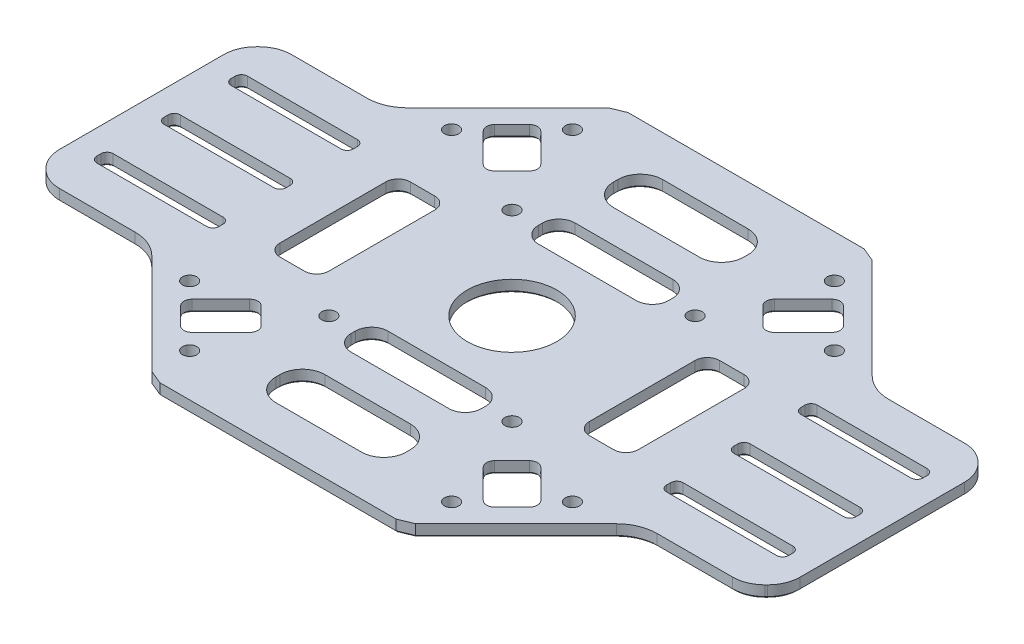
SolidWorks part; units mm, degrees
ref_plane "Спереди" through (0, 0, 0) normal (0, 0, 1) x (1, 0, 0)
ref_plane "Сверху" through (0, 0, 0) normal (0, 1, 0) x (1, 0, 0)
ref_plane "Справа" through (0, 0, 0) normal (1, 0, 0) x (0, 0, -1)
sketch "Эскиз1" plane through (0, 0, 0) normal (0, 1, 0) x (1, 0, 0)
  line L0 (-47.2118, 0) -> (134.7882, 0) construction
  line L1 (43.7882, -85.4485) -> (43.7882, 85.4485) construction
  line L2 (74.6039, 30.8143) -> (88.0389, 44.2493) construction
  line L3 (-47.2118, -20.1863) -> (-47.2118, 20.1863)
  line L4 (43.7882, 0) -> (74.6039, 30.8143) construction
  line L5 (59.7882, 23.5) -> (59.7882, 22.5)
  line L6 (-44.8686, 25.8431) -> (-44.5549, 26.1569)
  line L7 (72.7882, 57.5) -> (76.2024, 56.0858)
  line L8 (100.8593, 31.4289) -> (76.2024, 56.0858)
  line L9 (72.4825, 32.9356) -> (76.7252, 28.693)
  line L10 (86.6247, 35.7641) -> (79.5536, 28.693)
  line L11 (79.5536, 42.8351) -> (72.4825, 35.7641)
  line L12 (-38.8981, 28.5) -> (-20.3539, 28.5)
  line L13 (84.5034, 40.7138) -> (86.6247, 38.5925)
  line L14 (71.7882, 57.5) -> (15.7882, 57.5)
  line L15 (59.7882, 42) -> (59.7882, 41)
  line L16 (15.7882, 57.5) -> (14.7882, 57.5)
  line L17 (84.5034, 40.7138) -> (82.382, 42.8351)
  line L18 (75.7882, -13) -> (75.7882, 13)
  line L19 (-39.7118, 2) -> (-12.7118, 2)
  line L20 (-41.2118, 0.5) -> (-41.2118, -0.5)
  line L21 (84.7882, 16) -> (78.7882, 16)
  line L22 (-11.2118, 0.5) -> (-11.2118, -0.5)
  line L23 (87.7882, -13) -> (87.7882, 13)
  line L24 (100.2882, 18.5) -> (127.2882, 18.5)
  line L25 (127.2882, 14.5) -> (100.2882, 14.5)
  line L26 (128.7882, 17) -> (128.7882, 16)
  line L27 (98.7882, 16) -> (98.7882, 17)
  line L28 (98.7882, 0.5) -> (98.7882, -0.5)
  line L29 (128.7882, 0.5) -> (128.7882, -0.5)
  line L30 (127.2882, 2) -> (100.2882, 2)
  line L31 (71.7882, 57.5) -> (72.7882, 57.5)
  line L32 (126.4745, 28.5) -> (107.9304, 28.5)
  line L33 (132.4451, 25.8431) -> (132.1314, 26.1569)
  line L34 (134.7882, -20.1863) -> (134.7882, 20.1863)
  line L35 (12.9726, -30.8143) -> (-0.4624, -44.2493) construction
  line L36 (43.7882, 0) -> (12.9726, -30.8143) construction
  line L37 (43.7882, 0) -> (74.6039, -30.8143) construction
  line L38 (74.6039, -30.8143) -> (88.0389, -44.2493) construction
  line L39 (31.7882, -18.5) -> (55.7882, -18.5)
  line L40 (27.7882, -23.5) -> (27.7882, -22.5)
  line L41 (31.7882, -27.5) -> (55.7882, -27.5)
  line L42 (14.7882, -57.5) -> (11.374, -56.0858)
  line L43 (-13.2828, -31.4289) -> (11.374, -56.0858)
  line L44 (15.0939, -32.9356) -> (10.8513, -28.693)
  line L45 (0.9518, -35.7641) -> (8.0229, -28.693)
  line L46 (8.0229, -42.8351) -> (15.0939, -35.7641)
  line L47 (3.0731, -40.7138) -> (0.9518, -38.5925)
  line L48 (33.2882, -35.5) -> (54.2882, -35.5)
  line L49 (27.7882, -42) -> (27.7882, -41)
  line L50 (-11.2118, 16) -> (-11.2118, 17)
  line L51 (-41.2118, 17) -> (-41.2118, 16)
  line L52 (-39.7118, 14.5) -> (-12.7118, 14.5)
  line L53 (-12.7118, 18.5) -> (-39.7118, 18.5)
  line L54 (54.2882, -47.5) -> (33.2882, -47.5)
  line L55 (3.0731, -40.7138) -> (5.1944, -42.8351)
  line L56 (2.7882, -16) -> (8.7882, -16)
  line L57 (-12.7118, -18.5) -> (-39.7118, -18.5)
  line L58 (-39.7118, -14.5) -> (-12.7118, -14.5)
  line L59 (-41.2118, -17) -> (-41.2118, -16)
  line L60 (-11.2118, -16) -> (-11.2118, -17)
  line L61 (-0.2118, -13) -> (-0.2118, 13)
  line L62 (2.7882, 16) -> (8.7882, 16)
  line L63 (11.7882, -13) -> (11.7882, 13)
  line L64 (132.4451, -25.8431) -> (132.1314, -26.1569)
  line L65 (126.4745, -28.5) -> (107.9304, -28.5)
  line L66 (71.7882, -57.5) -> (72.7882, -57.5)
  line L67 (127.2882, -2) -> (100.2882, -2)
  line L68 (98.7882, -16) -> (98.7882, -17)
  line L69 (128.7882, -17) -> (128.7882, -16)
  line L70 (127.2882, -14.5) -> (100.2882, -14.5)
  line L71 (100.2882, -18.5) -> (127.2882, -18.5)
  line L72 (84.7882, -16) -> (78.7882, -16)
  line L73 (-39.7118, -2) -> (-12.7118, -2)
  line L74 (3.0731, 40.7138) -> (5.1944, 42.8351)
  line L75 (84.5034, -40.7138) -> (82.382, -42.8351)
  line L76 (54.2882, 47.5) -> (33.2882, 47.5)
  line L77 (27.7882, 42) -> (27.7882, 41)
  line L78 (33.2882, 35.5) -> (54.2882, 35.5)
  line L79 (15.7882, -57.5) -> (14.7882, -57.5)
  line L80 (3.0731, 40.7138) -> (0.9518, 38.5925)
  line L81 (8.0229, 42.8351) -> (15.0939, 35.7641)
  line L82 (0.9518, 35.7641) -> (8.0229, 28.693)
  line L83 (15.0939, 32.9356) -> (10.8513, 28.693)
  line L84 (59.7882, -42) -> (59.7882, -41)
  line L85 (71.7882, -57.5) -> (15.7882, -57.5)
  line L86 (84.5034, -40.7138) -> (86.6247, -38.5925)
  line L87 (-38.8981, -28.5) -> (-20.3539, -28.5)
  line L88 (79.5536, -42.8351) -> (72.4825, -35.7641)
  line L89 (86.6247, -35.7641) -> (79.5536, -28.693)
  line L90 (72.4825, -32.9356) -> (76.7252, -28.693)
  line L91 (100.8593, -31.4289) -> (76.2024, -56.0858)
  line L92 (72.7882, -57.5) -> (76.2024, -56.0858)
  line L93 (-44.8686, -25.8431) -> (-44.5549, -26.1569)
  line L94 (59.7882, -23.5) -> (59.7882, -22.5)
  line L102 (-13.2828, 31.4289) -> (11.374, 56.0858)
  line L103 (43.7882, 0) -> (12.9726, 30.8143) construction
  line L104 (12.9726, 30.8143) -> (-0.4624, 44.2493) construction
  line L107 (14.7882, 57.5) -> (11.374, 56.0858)
  line L110 (31.7882, 27.5) -> (55.7882, 27.5)
  line L111 (27.7882, 23.5) -> (27.7882, 22.5)
  line L112 (31.7882, 18.5) -> (55.7882, 18.5)
  circle A0 centre (43.7882, 0) radius 11
  arc A1 (-11.2118, 0.5) -> (-12.7118, 2) centre (-12.7118, 0.5) ccw
  arc A2 (-41.2118, 0.5) -> (-39.7118, 2) centre (-39.7118, 0.5) cw
  arc A3 (-44.8686, 25.8431) -> (-47.2118, 20.1863) centre (-39.2118, 20.1863) ccw
  arc A4 (-44.5549, 26.1569) -> (-38.8981, 28.5) centre (-38.8981, 20.5) cw
  arc A5 (59.7882, 42) -> (54.2882, 47.5) centre (54.2882, 42) ccw
  arc A6 (59.7882, 41) -> (54.2882, 35.5) centre (54.2882, 41) cw
  arc A7 (59.7882, 23.5) -> (55.7882, 27.5) centre (55.7882, 23.5) ccw
  arc A8 (59.7882, 22.5) -> (55.7882, 18.5) centre (55.7882, 22.5) cw
  arc A9 (107.9304, 28.5) -> (100.8593, 31.4289) centre (107.9304, 38.5) cw
  arc A10 (87.7882, 13) -> (84.7882, 16) centre (84.7882, 13) ccw
  arc A11 (78.7882, 16) -> (75.7882, 13) centre (78.7882, 13) ccw
  arc A12 (82.382, 42.8351) -> (79.5536, 42.8351) centre (80.9678, 41.4209) ccw
  arc A13 (72.4825, 35.7641) -> (72.4825, 32.9356) centre (73.8968, 34.3498) ccw
  arc A14 (79.5536, 28.693) -> (76.7252, 28.693) centre (78.1394, 30.1072) cw
  arc A15 (86.6247, 38.5925) -> (86.6247, 35.7641) centre (85.2105, 37.1783) cw
  arc A16 (-41.2118, 17) -> (-39.7118, 18.5) centre (-39.7118, 17) cw
  arc A17 (-41.2118, 16) -> (-39.7118, 14.5) centre (-39.7118, 16) ccw
  arc A18 (-11.2118, 16) -> (-12.7118, 14.5) centre (-12.7118, 16) cw
  arc A19 (-11.2118, 17) -> (-12.7118, 18.5) centre (-12.7118, 17) ccw
  arc A20 (98.7882, 17) -> (100.2882, 18.5) centre (100.2882, 17) cw
  arc A21 (98.7882, 16) -> (100.2882, 14.5) centre (100.2882, 16) ccw
  arc A22 (128.7882, 16) -> (127.2882, 14.5) centre (127.2882, 16) cw
  arc A23 (128.7882, 17) -> (127.2882, 18.5) centre (127.2882, 17) ccw
  arc A24 (132.1314, 26.1569) -> (126.4745, 28.5) centre (126.4745, 20.5) ccw
  arc A25 (132.4451, 25.8431) -> (134.7882, 20.1863) centre (126.7882, 20.1863) cw
  arc A26 (128.7882, 0.5) -> (127.2882, 2) centre (127.2882, 0.5) ccw
  arc A27 (98.7882, 0.5) -> (100.2882, 2) centre (100.2882, 0.5) cw
  arc A28 (0.9518, 38.5925) -> (0.9518, 35.7641) centre (2.366, 37.1783) ccw
  arc A29 (8.0229, 28.693) -> (10.8513, 28.693) centre (9.4371, 30.1072) ccw
  arc A30 (15.0939, 35.7641) -> (15.0939, 32.9356) centre (13.6797, 34.3498) cw
  arc A31 (5.1944, 42.8351) -> (8.0229, 42.8351) centre (6.6086, 41.4209) cw
  arc A32 (27.7882, -42) -> (33.2882, -47.5) centre (33.2882, -42) ccw
  arc A33 (27.7882, -41) -> (33.2882, -35.5) centre (33.2882, -41) cw
  arc A34 (27.7882, -23.5) -> (31.7882, -27.5) centre (31.7882, -23.5) ccw
  arc A35 (27.7882, -22.5) -> (31.7882, -18.5) centre (31.7882, -22.5) cw
  arc A36 (-20.3539, -28.5) -> (-13.2828, -31.4289) centre (-20.3539, -38.5) cw
  arc A37 (-0.2118, -13) -> (2.7882, -16) centre (2.7882, -13) ccw
  arc A38 (8.7882, -16) -> (11.7882, -13) centre (8.7882, -13) ccw
  arc A39 (5.1944, -42.8351) -> (8.0229, -42.8351) centre (6.6086, -41.4209) ccw
  arc A40 (15.0939, -35.7641) -> (15.0939, -32.9356) centre (13.6797, -34.3498) ccw
  arc A41 (8.0229, -28.693) -> (10.8513, -28.693) centre (9.4371, -30.1072) cw
  arc A42 (0.9518, -38.5925) -> (0.9518, -35.7641) centre (2.366, -37.1783) cw
  arc A43 (98.7882, -0.5) -> (100.2882, -2) centre (100.2882, -0.5) ccw
  arc A44 (128.7882, -0.5) -> (127.2882, -2) centre (127.2882, -0.5) cw
  arc A45 (132.4451, -25.8431) -> (134.7882, -20.1863) centre (126.7882, -20.1863) ccw
  arc A46 (132.1314, -26.1569) -> (126.4745, -28.5) centre (126.4745, -20.5) cw
  arc A47 (128.7882, -17) -> (127.2882, -18.5) centre (127.2882, -17) cw
  arc A48 (128.7882, -16) -> (127.2882, -14.5) centre (127.2882, -16) ccw
  arc A49 (98.7882, -16) -> (100.2882, -14.5) centre (100.2882, -16) cw
  arc A50 (8.7882, 16) -> (11.7882, 13) centre (8.7882, 13) cw
  arc A51 (-0.2118, 13) -> (2.7882, 16) centre (2.7882, 13) cw
  arc A52 (98.7882, -17) -> (100.2882, -18.5) centre (100.2882, -17) ccw
  arc A53 (-11.2118, -17) -> (-12.7118, -18.5) centre (-12.7118, -17) cw
  arc A54 (-11.2118, -16) -> (-12.7118, -14.5) centre (-12.7118, -16) ccw
  arc A55 (-41.2118, -16) -> (-39.7118, -14.5) centre (-39.7118, -16) cw
  arc A56 (-41.2118, -17) -> (-39.7118, -18.5) centre (-39.7118, -17) ccw
  arc A57 (86.6247, -38.5925) -> (86.6247, -35.7641) centre (85.2105, -37.1783) ccw
  arc A58 (79.5536, -28.693) -> (76.7252, -28.693) centre (78.1394, -30.1072) ccw
  arc A59 (72.4825, -35.7641) -> (72.4825, -32.9356) centre (73.8968, -34.3498) cw
  arc A60 (82.382, -42.8351) -> (79.5536, -42.8351) centre (80.9678, -41.4209) cw
  arc A61 (78.7882, -16) -> (75.7882, -13) centre (78.7882, -13) cw
  arc A62 (87.7882, -13) -> (84.7882, -16) centre (84.7882, -13) cw
  arc A63 (-20.3539, 28.5) -> (-13.2828, 31.4289) centre (-20.3539, 38.5) ccw
  arc A64 (107.9304, -28.5) -> (100.8593, -31.4289) centre (107.9304, -38.5) ccw
  arc A65 (59.7882, -22.5) -> (55.7882, -18.5) centre (55.7882, -22.5) ccw
  arc A66 (27.7882, 22.5) -> (31.7882, 18.5) centre (31.7882, 22.5) ccw
  arc A67 (27.7882, 23.5) -> (31.7882, 27.5) centre (31.7882, 23.5) cw
  arc A68 (27.7882, 41) -> (33.2882, 35.5) centre (33.2882, 41) ccw
  arc A69 (27.7882, 42) -> (33.2882, 47.5) centre (33.2882, 42) cw
  arc A70 (59.7882, -23.5) -> (55.7882, -27.5) centre (55.7882, -23.5) cw
  arc A71 (59.7882, -41) -> (54.2882, -35.5) centre (54.2882, -41) ccw
  arc A72 (59.7882, -42) -> (54.2882, -47.5) centre (54.2882, -42) cw
  arc A73 (-44.5549, -26.1569) -> (-38.8981, -28.5) centre (-38.8981, -20.5) ccw
  arc A74 (-44.8686, -25.8431) -> (-47.2118, -20.1863) centre (-39.2118, -20.1863) cw
  arc A75 (-41.2118, -0.5) -> (-39.7118, -2) centre (-39.7118, -0.5) ccw
  arc A76 (-11.2118, -0.5) -> (-12.7118, -2) centre (-12.7118, -0.5) cw
  point P5 (-47.2118, 23.5)
  point P8 (-47.2118, 28.5)
  point P11 (103.7882, 28.5)
  point P13 (-42.2118, 28.5)
  point P14 (43.7882, 18.5)
  point P16 (43.7882, 47.5)
  point P28 (-41.2118, 0)
  point P36 (12.7882, 57.5)
  point P65 (-0.2118, 0)
  point P76 (75.7882, 0)
  point P105 (43.7882, 27.5)
  point P109 (43.7882, 35.5)
  point P110 (-11.2118, 0)
  point P111 (87.7882, 0)
  point P112 (98.7882, 0)
  point P114 (43.7882, 57.5)
  point P115 (87.7882, 16)
  point P116 (75.7882, 16)
  point P117 (80.9678, 44.2493)
  point P118 (71.0683, 34.3498)
  point P119 (78.1394, 27.2788)
  point P120 (88.0389, 37.1783)
  point P121 (98.7882, 18.5)
  point P122 (98.7882, 14.5)
  point P123 (128.7882, 14.5)
  point P124 (128.7882, 18.5)
  point P125 (74.7882, 57.5)
  point P126 (129.7882, 28.5)
  point P127 (134.7882, 28.5)
  point P128 (134.7882, 23.5)
  point P148 (-41.2118, 18.5)
  point P151 (-41.2118, 14.5)
  point P154 (-11.2118, 14.5)
  point P157 (-11.2118, 18.5)
  point P184 (-0.4624, 37.1783)
  point P187 (9.4371, 27.2788)
  point P190 (16.5081, 34.3498)
  point P193 (6.6086, 44.2493)
  point P250 (11.7882, 16)
  point P253 (-0.2118, 16)
  point P280 (11.7882, 0)
  point P282 (128.7882, 0)
  point P285 (-16.2118, -28.5)
  point P286 (-0.2118, -16)
  point P287 (11.7882, -16)
  point P288 (6.6086, -44.2493)
  point P289 (16.5081, -34.3498)
  point P290 (9.4371, -27.2788)
  point P293 (-16.2118, 28.5)
  point P294 (-0.4624, -37.1783)
  point P295 (-11.2118, -18.5)
  point P296 (-11.2118, -14.5)
  point P297 (-41.2118, -14.5)
  point P298 (-41.2118, -18.5)
  point P301 (134.7882, -23.5)
  point P302 (134.7882, -28.5)
  point P304 (129.7882, -28.5)
  point P307 (74.7882, -57.5)
  point P317 (128.7882, -18.5)
  point P318 (128.7882, -14.5)
  point P319 (98.7882, -14.5)
  point P320 (98.7882, -18.5)
  point P321 (88.0389, -37.1783)
  point P322 (78.1394, -27.2788)
  point P323 (71.0683, -34.3498)
  point P324 (80.9678, -44.2493)
  point P325 (75.7882, -16)
  point P326 (87.7882, -16)
  point P327 (43.7882, -57.5)
  point P328 (43.7882, -35.5)
  point P329 (43.7882, -27.5)
  point P330 (12.7882, -57.5)
  point P331 (43.7882, -47.5)
  point P332 (43.7882, -18.5)
  point P333 (-42.2118, -28.5)
  point P334 (103.7882, -28.5)
  point P335 (-47.2118, -28.5)
  point P336 (-47.2118, -23.5)
  dimension "D19" = 2
  dimension "D21" = 2
  dimension "D32" = 4
  dimension "D36" = 5.5
  dimension "D9" = 22
  dimension "D38" = 1.5
  dimension "D4" = 8
  dimension "D2" = 5
  dimension "D3" = 14
  dimension "D6" = 31
  dimension "D10" = 57.5
  dimension "D31" = 9
  dimension "D35" = 8
  dimension "D37" = 47
extrude "Бобышка-Вытянуть1" add sketch "Эскиз1" along normal blind 3
sketch "Эскиз2" plane through (0, 3, 0) normal (0, 1, 0) x (1, 0, 0)
  line L0 (43.7882, 57.5) -> (43.7882, -60.5) construction
  line L1 (72.7882, 57.5) -> (14.7882, 57.5) construction
  line L2 (134.7882, 0) -> (-47.2118, 0) construction
  line L3 (134.7882, -23.5) -> (134.7882, 23.5) construction
  line L4 (-47.2118, 20.1863) -> (-47.2118, -20.1863) construction
  line L5 (43.7882, 0) -> (-0.4618, 44.25) construction
  line L6 (11.374, 56.0858) -> (-13.2828, 31.4289) construction
  line L7 (43.7882, 0) -> (88.0382, -44.25) construction
  line L8 (79.1106, -53.1777) -> (100.8593, -31.4289) construction
  line L9 (43.7882, 0) -> (-0.4618, -44.25) construction
  line L10 (-13.2828, -31.4289) -> (8.5298, -53.2416) construction
  line L11 (43.7882, 0) -> (88.0382, 44.25) construction
  line L12 (100.8593, 31.4289) -> (76.2024, 56.0858) construction
  line L14 (4.1902, 39.598) -> (11.6149, 47.0226) construction
  line L15 (4.1902, 39.598) -> (-3.2344, 32.1734) construction
  line L16 (-42.2118, -28.5) -> (-20.3539, -28.5) construction
  line L17 (-20.3539, 28.5) -> (-38.8981, 28.5) construction
  circle A0 centre (11.6149, 47.0226) radius 1.75
  circle A1 centre (-3.2344, 32.1734) radius 1.75
  circle A2 centre (75.9616, 47.0226) radius 1.75
  circle A3 centre (90.8108, 32.1734) radius 1.75
  circle A4 centre (90.8108, -32.1734) radius 1.75
  circle A5 centre (75.9616, -47.0226) radius 1.75
  circle A6 centre (11.6149, -47.0226) radius 1.75
  circle A7 centre (-3.2344, -32.1734) radius 1.75
  point P41 (-31.2828, -28.5)
  dimension "D1" = 10.5
  dimension "D3" = 3.5
  dimension "D6" = 32.1734
  dimension "D2" = 90
  dimension "D4" = 10.5
  dimension "D5" = 90
  dimension "D7" = 47.0226
  dimension "D14" = 118
  dimension "D15" = 57.5
  dimension "D16" = 60.5
  dimension "D17" = 57
extrude "Вырез-Вытянуть1" cut sketch "Эскиз2" against normal blind 10
chamfer "Chaflán1" distance 0.5 angle 45 169 edges at (43.7882, 0, 11) (113.7882, 0, 18.5) (99.2276, 0, 18.0607) (98.7882, 0, 16.5) (99.2276, 0, 14.9393) (113.7882, 0, 14.5) (128.3489, 0, 14.9393) (128.7882, 0, 16.5) (128.3489, 0, 18.0607) (-0.2118, 0, 0) (0.6669, 0, -15.1213) (5.7882, 0, -16) (10.9096, 0, -15.1213) (11.7882, 0, 0) (10.9096, 0, 15.1213) (5.7882, 0, 16) (0.6669, 0, 15.1213) (27.7882, 0, 23) (28.9598, 0, 19.6716) (43.7882, 0, 18.5) (58.6167, 0, 19.6716) (59.7882, 0, 23) (58.6167, 0, 26.3284) (43.7882, 0, 27.5) (28.9598, 0, 26.3284) (128.7882, 0, 0) (128.3489, 0, 1.5607) (113.7882, 0, 2) (99.2276, 0, 1.5607) (98.7882, 0, 0) (99.2276, 0, -1.5607) (113.7882, 0, -2) (128.3489, 0, -1.5607) (84.5034, 0, 40.7138) (80.9678, 0, 43.4209) (76.0181, 0, 39.2996) (71.8968, 0, 34.3498) (74.6039, 0, 30.8143) (78.1394, 0, 28.1072) (83.0891, 0, 32.2285) (87.2105, 0, 37.1783) (84.5034, 0, -40.7138) (87.2105, 0, -37.1783) (83.0891, 0, -32.2285) (78.1394, 0, -28.1072) (74.6039, 0, -30.8143) (71.8968, 0, -34.3498) (76.0181, 0, -39.2996) (80.9678, 0, -43.4209) (59.7882, 0, -23) (58.6167, 0, -19.6716) (43.7882, 0, -18.5) (28.9598, 0, -19.6716) (27.7882, 0, -23) (28.9598, 0, -26.3284) (43.7882, 0, -27.5) (58.6167, 0, -26.3284) (59.7882, 0, -41.5) (58.1773, 0, -37.1109) (43.7882, 0, -35.5) (29.3991, 0, -37.1109) (27.7882, 0, -41.5) (29.3991, 0, -45.8891) (43.7882, 0, -47.5) (58.1773, 0, -45.8891) (-47.2118, 0, 0) (-46.6028, 0, 23.2478) (-44.7118, 0, 26) (-41.9595, 0, 27.891) (-29.626, 0, 28.5) (-16.5271, 0, 29.2612) (-0.9544, 0, 43.7574) (13.0811, 0, 56.7929) (43.7882, 0, 57.5) (74.4953, 0, 56.7929) (88.5309, 0, 43.7574) (104.1035, 0, 29.2612) (117.2024, 0, 28.5) (129.536, 0, 27.891) (132.2882, 0, 26) (134.1793, 0, 23.2478) (134.7882, 0, 0) (134.1793, 0, -23.2478) (132.2882, 0, -26) (129.536, 0, -27.891) (117.2024, 0, -28.5) (104.1035, 0, -29.2612) (88.5309, 0, -43.7574) (74.4953, 0, -56.7929) (43.7882, 0, -57.5) (13.0811, 0, -56.7929) (-0.9544, 0, -43.7574) (-16.5271, 0, -29.2612) (-29.626, 0, -28.5) (-41.9595, 0, -27.891) (-44.7118, 0, -26) (-46.6028, 0, -23.2478) (-11.2118, 0, 0) (-11.6511, 0, 1.5607) (-26.2118, 0, 2) (-40.7724, 0, 1.5607) (-41.2118, 0, 0) (-40.7724, 0, -1.5607) (-26.2118, 0, -2) (-11.6511, 0, -1.5607) (87.7882, 0, 0) (86.9096, 0, 15.1213) (81.7882, 0, 16) (76.6669, 0, 15.1213) (75.7882, 0, 0) (76.6669, 0, -15.1213) (81.7882, 0, -16) (86.9096, 0, -15.1213) (113.7882, 0, -18.5) (128.3489, 0, -18.0607) (128.7882, 0, -16.5) (128.3489, 0, -14.9393) (113.7882, 0, -14.5) (99.2276, 0, -14.9393) (98.7882, 0, -16.5) (99.2276, 0, -18.0607) (3.0731, 0, -40.7138) (6.6086, 0, -43.4209) (11.5584, 0, -39.2996) (15.6797, 0, -34.3498) (12.9726, 0, -30.8143) (9.4371, 0, -28.1072) (4.4873, 0, -32.2285) (0.366, 0, -37.1783) (27.7882, 0, 41.5) (29.3991, 0, 37.1109) (43.7882, 0, 35.5) (58.1773, 0, 37.1109) (59.7882, 0, 41.5) (58.1773, 0, 45.8891) (43.7882, 0, 47.5) (29.3991, 0, 45.8891) (-26.2118, 0, -18.5) (-11.6511, 0, -18.0607) (-11.2118, 0, -16.5) (-11.6511, 0, -14.9393) (-26.2118, 0, -14.5) (-40.7724, 0, -14.9393) (-41.2118, 0, -16.5) (-40.7724, 0, -18.0607) (3.0731, 0, 40.7138) (0.366, 0, 37.1783) (4.4873, 0, 32.2285) (9.4371, 0, 28.1072) (12.9726, 0, 30.8143) (15.6797, 0, 34.3498) (11.5584, 0, 39.2996) (6.6086, 0, 43.4209) (-26.2118, 0, 18.5) (-40.7724, 0, 18.0607) (-41.2118, 0, 16.5) (-40.7724, 0, 14.9393) (-26.2118, 0, 14.5) (-11.6511, 0, 14.9393) (-11.2118, 0, 16.5) (-11.6511, 0, 18.0607) (11.6149, 0, -45.2726) (-3.2344, 0, -30.4234) (75.9616, 0, -45.2726) (90.8108, 0, -30.4234) (90.8108, 0, 33.9234) (75.9616, 0, 48.7726) (11.6149, 0, 48.7726) (-3.2344, 0, 33.9234)
sketch "Croquis1" plane through (0, 3, 0) normal (0, 1, 0) x (1, 0, 0)
  line L0 (43.7882, 0) -> (43.7882, -14.2245) construction
  line L1 (43.7882, 0) -> (62.8104, 0) construction
  circle A0 centre (21.2882, 22.5) radius 1.75
  circle A1 centre (43.7882, 0) radius 11 construction
  circle A2 centre (66.2882, 22.5) radius 1.75
  circle A3 centre (66.2882, -22.5) radius 1.75
  circle A4 centre (21.2882, -22.5) radius 1.75
  dimension "D1" = 3.5
  dimension "D2" = 22.5
  dimension "D3" = 22.5
extrude "Cortar-Extruir1" cut sketch "Croquis1" against normal up to next
chamfer "Chaflán2" distance 0.5 angle 45 4 edges at (66.2882, 0, -20.75) (66.2882, 0, 24.25) (21.2882, 0, 24.25) (21.2882, 0, -20.75)
equation "\"D3@Croquis1\"=\"D2@Croquis1\""
